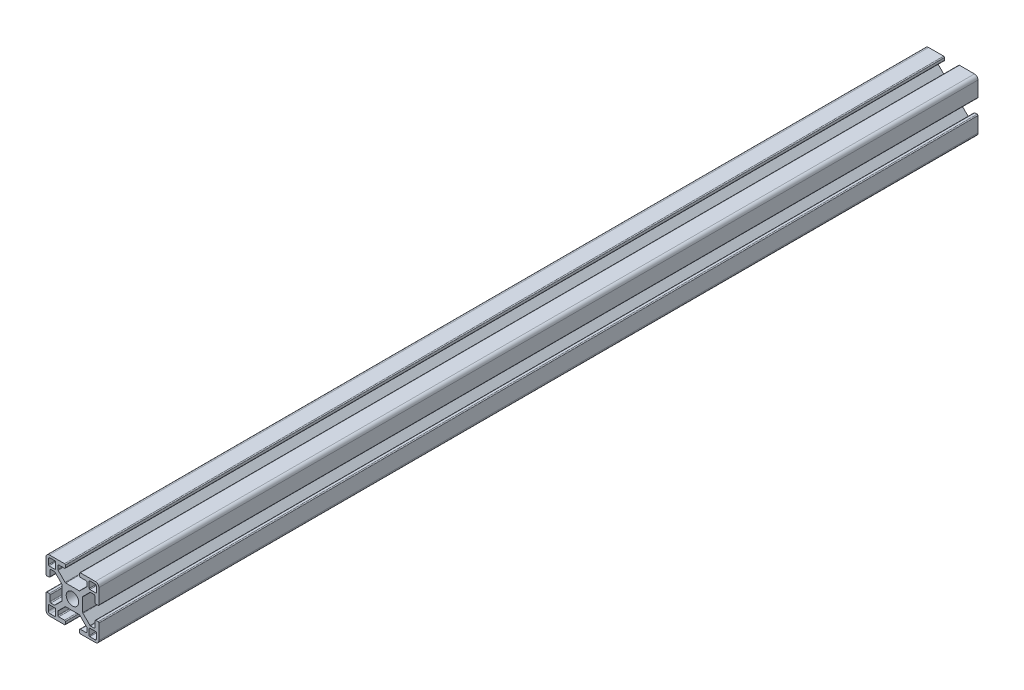
SolidWorks part; units mm, degrees
ref_plane "Front Plane" through (0, 0, 0) normal (0, 0, 1) x (1, 0, 0)
ref_plane "Top Plane" through (0, 0, 0) normal (0, 1, 0) x (1, 0, 0)
ref_plane "Right Plane" through (0, 0, 0) normal (1, 0, 0) x (0, 0, -1)
sketch "Sketch1" plane through (0, 0, 0) normal (0, 0, 1) x (1, 0, 0)
  line L0 (3.9799, -2.4733) -> (3.1981, -1.4942) construction
  line L1 (1.4942, -3.1981) -> (2.4733, -3.9799) construction
  line L2 (-2.4733, -3.9799) -> (-1.4942, -3.1981) construction
  line L3 (-3.1981, -1.4942) -> (-3.9799, -2.4733) construction
  line L4 (-3.9799, 2.4733) -> (-3.1981, 1.4942) construction
  line L5 (-1.4942, 3.1981) -> (-2.4733, 3.9799) construction
  line L6 (2.4733, 3.9799) -> (1.4942, 3.1981) construction
  line L7 (3.1981, 1.4942) -> (3.9799, 2.4733) construction
  line L8 (-12.6999, -13.6999) -> (-9.881, -13.6999)
  line L9 (-13.6999, -9.881) -> (-13.6999, -12.6999)
  line L10 (-9.88, -9.5) -> (-13.3189, -9.5)
  line L11 (-9.5, -13.3189) -> (-9.5, -9.88)
  line L12 (13.6999, -12.6999) -> (13.6999, -9.881)
  line L13 (9.881, -13.6999) -> (12.6999, -13.6999)
  line L14 (9.5, -9.88) -> (9.5, -13.3189)
  line L15 (13.3189, -9.5) -> (9.88, -9.5)
  line L16 (9.88, 9.5) -> (13.3189, 9.5)
  line L17 (9.5, 13.3189) -> (9.5, 9.88)
  line L18 (12.6999, 13.6999) -> (9.881, 13.6999)
  line L19 (13.6999, 9.881) -> (13.6999, 12.6999)
  line L20 (-13.6999, 12.6999) -> (-13.6999, 9.881)
  line L21 (-9.881, 13.6999) -> (-12.6999, 13.6999)
  line L22 (-9.5, 9.88) -> (-9.5, 13.3189)
  line L23 (-13.3189, 9.5) -> (-9.88, 9.5)
  line L24 (14.4999, -4) -> (13.2425, -4)
  line L25 (12.7425, -4.5) -> (12.7425, -7.7325)
  line L26 (12.2428, -8.25) -> (10.2602, -8.25)
  line L27 (9.9066, -8.1035) -> (5.9811, -4.178)
  line L28 (5.8347, -3.8245) -> (5.8347, -1.0125)
  line L29 (5.8347, -1.0125) -> (5.3247, -0.0625) construction
  line L30 (5.3247, -0.0625) -> (5.8347, 0.8875) construction
  line L31 (5.8347, 0.8875) -> (5.8347, 3.8245)
  line L32 (5.9811, 4.178) -> (9.9066, 8.1035)
  line L33 (10.2602, 8.25) -> (12.2428, 8.25)
  line L34 (12.7425, 7.7325) -> (12.7425, 4.5)
  line L35 (13.2425, 4) -> (14.4999, 4)
  line L36 (14.9999, 4.5) -> (14.9999, 12.9999)
  line L37 (12.9999, 14.9999) -> (4.5, 14.9999)
  line L38 (4, 14.4999) -> (4, 13.2425)
  line L39 (4.5, 12.7425) -> (7.7325, 12.7425)
  line L40 (8.25, 12.2428) -> (8.25, 10.2602)
  line L41 (8.1035, 9.9066) -> (4.178, 5.9811)
  line L42 (3.8245, 5.8347) -> (0.95, 5.8347)
  line L43 (0.95, 5.8347) -> (0, 5.3247) construction
  line L44 (0, 5.3247) -> (-0.95, 5.8347) construction
  line L45 (-0.95, 5.8347) -> (-3.8245, 5.8347)
  line L46 (-4.178, 5.9811) -> (-8.1035, 9.9066)
  line L47 (-8.25, 10.2602) -> (-8.25, 12.2428)
  line L48 (-7.7325, 12.7425) -> (-4.5, 12.7425)
  line L49 (-4, 13.2425) -> (-4, 14.4999)
  line L50 (-4.5, 14.9999) -> (-12.9999, 14.9999)
  line L51 (-14.9999, 12.9999) -> (-14.9999, 4.5)
  line L52 (-14.4999, 4) -> (-13.2425, 4)
  line L53 (-12.7425, 4.5) -> (-12.7425, 7.7325)
  line L54 (-12.2428, 8.25) -> (-10.2602, 8.25)
  line L55 (-9.9066, 8.1035) -> (-5.9811, 4.178)
  line L56 (-5.8347, 3.8245) -> (-5.8347, 0.8875)
  line L57 (-5.8347, 0.8875) -> (-5.3247, -0.0625) construction
  line L58 (-5.3247, -0.0625) -> (-5.8347, -1.0125) construction
  line L59 (-5.8347, -1.0125) -> (-5.8347, -3.8245)
  line L60 (-5.9811, -4.178) -> (-9.9066, -8.1035)
  line L61 (-10.2602, -8.25) -> (-12.2428, -8.25)
  line L62 (-12.7425, -7.7325) -> (-12.7425, -4.5)
  line L63 (-13.2425, -4) -> (-14.4999, -4)
  line L64 (-14.9999, -4.5) -> (-14.9999, -12.9999)
  line L65 (-12.9999, -14.9999) -> (-4.5, -14.9999)
  line L66 (-4, -14.4999) -> (-4, -13.2425)
  line L67 (-4.5, -12.7425) -> (-7.7325, -12.7425)
  line L68 (-8.25, -12.2428) -> (-8.25, -10.2602)
  line L69 (-8.1035, -9.9066) -> (-4.178, -5.9811)
  line L70 (-3.8245, -5.8347) -> (-0.95, -5.8347)
  line L71 (-0.95, -5.8347) -> (0, -5.3247) construction
  line L72 (0, -5.3247) -> (0.95, -5.8347) construction
  line L73 (0.95, -5.8347) -> (3.8245, -5.8347)
  line L74 (4.178, -5.9811) -> (8.1035, -9.9066)
  line L75 (8.25, -10.2602) -> (8.25, -12.2428)
  line L76 (7.7325, -12.7425) -> (4.5, -12.7425)
  line L77 (4, -13.2425) -> (4, -14.4999)
  line L78 (4.5, -14.9999) -> (12.9999, -14.9999)
  line L79 (14.9999, -12.9999) -> (14.9999, -4.5)
  line L80 (-5.8347, -1.0125) -> (-5.8347, 0.8875)
  line L81 (-0.95, 5.8347) -> (0.95, 5.8347)
  line L82 (5.8347, 0.8875) -> (5.8347, -1.0125)
  line L83 (-0.95, -5.8347) -> (0.95, -5.8347)
  arc A0 (2.4733, -3.9799) -> (3.9799, -2.4733) centre (3.1422, -3.1422) ccw construction
  arc A1 (-1.4942, -3.1981) -> (1.4942, -3.1981) centre (0, 0) ccw construction
  arc A2 (-3.9799, -2.4733) -> (-2.4733, -3.9799) centre (-3.1422, -3.1422) ccw construction
  arc A3 (-3.1981, 1.4942) -> (-3.1981, -1.4942) centre (0, 0) ccw construction
  arc A4 (-2.4733, 3.9799) -> (-3.9799, 2.4733) centre (-3.1422, 3.1422) ccw construction
  arc A5 (1.4942, 3.1981) -> (-1.4942, 3.1981) centre (0, 0) ccw construction
  arc A6 (3.9799, 2.4733) -> (2.4733, 3.9799) centre (3.1422, 3.1422) ccw construction
  arc A7 (3.1981, -1.4942) -> (3.1981, 1.4942) centre (0, 0) ccw construction
  arc A8 (-13.6999, -12.6999) -> (-12.6999, -13.6999) centre (-12.6999, -12.6999) ccw
  arc A9 (-13.3189, -9.5) -> (-13.6999, -9.881) centre (-13.3189, -9.881) ccw
  arc A10 (-9.5, -9.88) -> (-9.88, -9.5) centre (-9.88, -9.88) ccw
  arc A11 (-9.881, -13.6999) -> (-9.5, -13.3189) centre (-9.881, -13.3189) ccw
  arc A12 (12.6999, -13.6999) -> (13.6999, -12.6999) centre (12.6999, -12.6999) ccw
  arc A13 (9.5, -13.3189) -> (9.881, -13.6999) centre (9.881, -13.3189) ccw
  arc A14 (9.88, -9.5) -> (9.5, -9.88) centre (9.88, -9.88) ccw
  arc A15 (13.6999, -9.881) -> (13.3189, -9.5) centre (13.3189, -9.881) ccw
  arc A16 (9.5, 9.88) -> (9.88, 9.5) centre (9.88, 9.88) ccw
  arc A17 (9.881, 13.6999) -> (9.5, 13.3189) centre (9.881, 13.3189) ccw
  arc A18 (13.6999, 12.6999) -> (12.6999, 13.6999) centre (12.6999, 12.6999) ccw
  arc A19 (13.3189, 9.5) -> (13.6999, 9.881) centre (13.3189, 9.881) ccw
  arc A20 (14.9999, -4.5) -> (14.4999, -4) centre (14.4999, -4.5) ccw
  arc A21 (13.2425, -4) -> (12.7425, -4.5) centre (13.2425, -4.5) ccw
  arc A22 (12.2428, -8.25) -> (12.7425, -7.7325) centre (12.2428, -7.75) ccw
  arc A23 (9.9066, -8.1035) -> (10.2602, -8.25) centre (10.2602, -7.75) ccw
  arc A24 (5.8347, -3.8245) -> (5.9811, -4.178) centre (6.3347, -3.8245) ccw
  arc A25 (5.9811, 4.178) -> (5.8347, 3.8245) centre (6.3347, 3.8245) ccw
  arc A26 (10.2602, 8.25) -> (9.9066, 8.1035) centre (10.2602, 7.75) ccw
  arc A27 (12.7425, 7.7325) -> (12.2428, 8.25) centre (12.2428, 7.75) ccw
  arc A28 (12.7425, 4.5) -> (13.2425, 4) centre (13.2425, 4.5) ccw
  arc A29 (14.4999, 4) -> (14.9999, 4.5) centre (14.4999, 4.5) ccw
  arc A30 (14.9999, 12.9999) -> (12.9999, 14.9999) centre (12.9999, 12.9999) ccw
  arc A31 (4.5, 14.9999) -> (4, 14.4999) centre (4.5, 14.4999) ccw
  arc A32 (4, 13.2425) -> (4.5, 12.7425) centre (4.5, 13.2425) ccw
  arc A33 (8.25, 12.2428) -> (7.7325, 12.7425) centre (7.75, 12.2428) ccw
  arc A34 (8.1035, 9.9066) -> (8.25, 10.2602) centre (7.75, 10.2602) ccw
  arc A35 (3.8245, 5.8347) -> (4.178, 5.9811) centre (3.8245, 6.3347) ccw
  arc A36 (-4.178, 5.9811) -> (-3.8245, 5.8347) centre (-3.8245, 6.3347) ccw
  arc A37 (-8.25, 10.2602) -> (-8.1035, 9.9066) centre (-7.75, 10.2602) ccw
  arc A38 (-7.7325, 12.7425) -> (-8.25, 12.2428) centre (-7.75, 12.2428) ccw
  arc A39 (-4.5, 12.7425) -> (-4, 13.2425) centre (-4.5, 13.2425) ccw
  arc A40 (-4, 14.4999) -> (-4.5, 14.9999) centre (-4.5, 14.4999) ccw
  arc A41 (-12.9999, 14.9999) -> (-14.9999, 12.9999) centre (-12.9999, 12.9999) ccw
  arc A42 (-14.9999, 4.5) -> (-14.4999, 4) centre (-14.4999, 4.5) ccw
  arc A43 (-13.2425, 4) -> (-12.7425, 4.5) centre (-13.2425, 4.5) ccw
  arc A44 (-12.2428, 8.25) -> (-12.7425, 7.7325) centre (-12.2428, 7.75) ccw
  arc A45 (-9.9066, 8.1035) -> (-10.2602, 8.25) centre (-10.2602, 7.75) ccw
  arc A46 (-5.8347, 3.8245) -> (-5.9811, 4.178) centre (-6.3347, 3.8245) ccw
  arc A47 (-5.9811, -4.178) -> (-5.8347, -3.8245) centre (-6.3347, -3.8245) ccw
  arc A48 (-10.2602, -8.25) -> (-9.9066, -8.1035) centre (-10.2602, -7.75) ccw
  arc A49 (-12.7425, -7.7325) -> (-12.2428, -8.25) centre (-12.2428, -7.75) ccw
  arc A50 (-12.7425, -4.5) -> (-13.2425, -4) centre (-13.2425, -4.5) ccw
  arc A51 (-14.4999, -4) -> (-14.9999, -4.5) centre (-14.4999, -4.5) ccw
  arc A52 (-14.9999, -12.9999) -> (-12.9999, -14.9999) centre (-12.9999, -12.9999) ccw
  arc A53 (-4.5, -14.9999) -> (-4, -14.4999) centre (-4.5, -14.4999) ccw
  arc A54 (-4, -13.2425) -> (-4.5, -12.7425) centre (-4.5, -13.2425) ccw
  arc A55 (-8.25, -12.2428) -> (-7.7325, -12.7425) centre (-7.75, -12.2428) ccw
  arc A56 (-8.1035, -9.9066) -> (-8.25, -10.2602) centre (-7.75, -10.2602) ccw
  arc A57 (-3.8245, -5.8347) -> (-4.178, -5.9811) centre (-3.8245, -6.3347) ccw
  arc A58 (4.178, -5.9811) -> (3.8245, -5.8347) centre (3.8245, -6.3347) ccw
  arc A59 (8.25, -10.2602) -> (8.1035, -9.9066) centre (7.75, -10.2602) ccw
  arc A60 (7.7325, -12.7425) -> (8.25, -12.2428) centre (7.75, -12.2428) ccw
  arc A61 (4.5, -12.7425) -> (4, -13.2425) centre (4.5, -13.2425) ccw
  arc A62 (4, -14.4999) -> (4.5, -14.9999) centre (4.5, -14.4999) ccw
  arc A63 (12.9999, -14.9999) -> (14.9999, -12.9999) centre (12.9999, -12.9999) ccw
  arc A64 (-12.6999, 13.6999) -> (-13.6999, 12.6999) centre (-12.6999, 12.6999) ccw
  arc A65 (-9.5, 13.3189) -> (-9.881, 13.6999) centre (-9.881, 13.3189) ccw
  arc A66 (-9.88, 9.5) -> (-9.5, 9.88) centre (-9.88, 9.88) ccw
  arc A67 (-13.6999, 9.881) -> (-13.3189, 9.5) centre (-13.3189, 9.881) ccw
  circle A68 centre (0, 0) radius 3.53
extrude "Boss-Extrude1" add sketch "Sketch1" along normal mid plane 498.64
